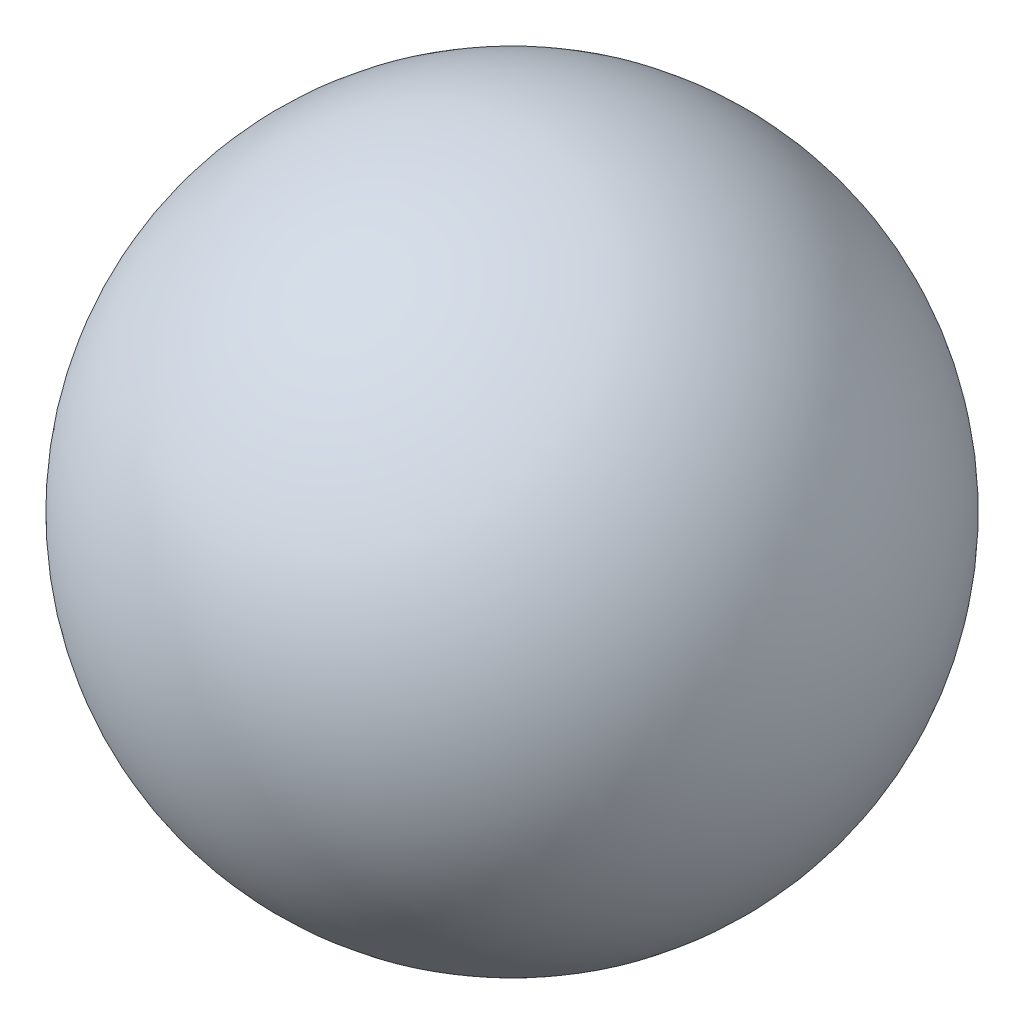
SolidWorks part; units mm, degrees
ref_plane "Front Plane" through (0, 0, 0) normal (0, 0, 1) x (1, 0, 0)
ref_plane "Top Plane" through (0, 0, 0) normal (0, 1, 0) x (1, 0, 0)
ref_plane "Right Plane" through (0, 0, 0) normal (1, 0, 0) x (0, 0, -1)
sketch "Sketch1" plane through (0, 0, 0) normal (0, 0, 1) x (1, 0, 0)
  line L0 (0, 105.0842) -> (0, -101.9811) construction
  line L1 (0, 80) -> (0, 76)
  line L2 (0, -76) -> (0, -80)
  arc A0 (0, 80) -> (0, -80) centre (0, 0) ccw
  arc A1 (0, 76) -> (0, -76) centre (0, 0) ccw
  dimension "D1" = 80
  dimension "D2" = 4
revolve "Revolve1" add sketch "Sketch1" angle 360 about L0
